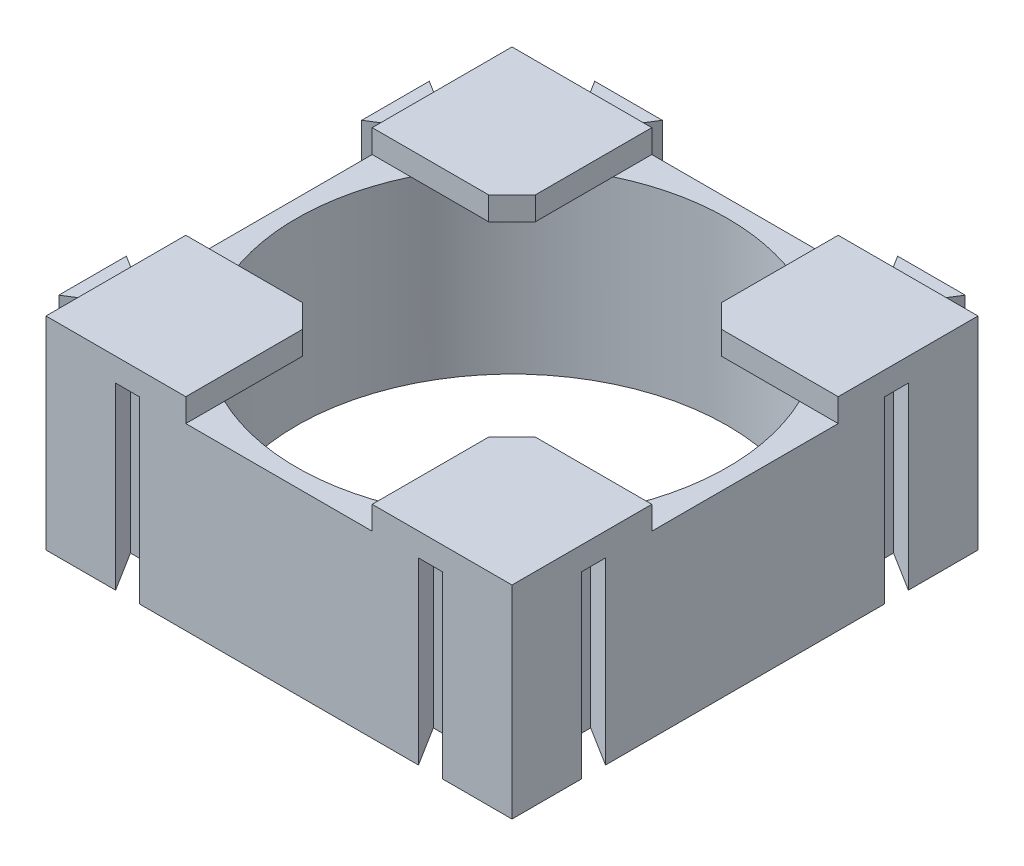
SolidWorks part; units mm, degrees
ref_plane "Alzado" through (0, 0, 0) normal (0, 0, 1) x (1, 0, 0)
ref_plane "Planta" through (0, 0, 0) normal (0, 1, 0) x (1, 0, 0)
ref_plane "Vista lateral" through (0, 0, 0) normal (1, 0, 0) x (0, 0, -1)
ref_plane "Plano1" through (0, 7.7, 0) normal (0, 1, 0) x (1, 0, 0)
sketch "Croquis1" plane through (0, 7.7, 0) normal (0, 1, 0) x (1, 0, 0)
  line L0 (5.9873, -10) -> (4.925, -8.3)
  line L1 (4.925, -8.3) -> (8.075, -8.3)
  line L2 (8.075, -8.3) -> (7.0127, -10)
  line L3 (7.0127, -10) -> (10, -10)
  line L4 (10, -10) -> (10, -7.0127)
  line L5 (10, -7.0127) -> (8.3, -8.075)
  line L6 (8.3, -8.075) -> (8.3, -4.925)
  line L7 (8.3, -4.925) -> (10, -5.9873)
  line L8 (10, -5.9873) -> (10, 5.9873)
  line L9 (10, 5.9873) -> (8.3, 4.925)
  line L10 (8.3, 4.925) -> (8.3, 8.075)
  line L11 (8.3, 8.075) -> (10, 7.0127)
  line L12 (10, 7.0127) -> (10, 10)
  line L13 (10, 10) -> (7.0127, 10)
  line L14 (7.0127, 10) -> (7.95, 11.5)
  line L15 (7.95, 11.5) -> (5.05, 11.5)
  line L16 (5.05, 11.5) -> (5.9873, 10)
  line L17 (5.9873, 10) -> (-5.9873, 10)
  line L18 (-5.9873, 10) -> (-5.05, 11.5)
  line L19 (-5.05, 11.5) -> (-7.95, 11.5)
  line L20 (-7.95, 11.5) -> (-7.0127, 10)
  line L21 (-7.0127, 10) -> (-10, 10)
  line L22 (-10, 10) -> (-10, 7.0127)
  line L23 (-10, 7.0127) -> (-11.5, 7.95)
  line L24 (-11.5, 7.95) -> (-11.5, 5.05)
  line L25 (-11.5, 5.05) -> (-10, 5.9873)
  line L26 (-10, 5.9873) -> (-10, -5.9873)
  line L27 (-10, -5.9873) -> (-11.5, -5.05)
  line L28 (-11.5, -5.05) -> (-11.5, -7.95)
  line L29 (-11.5, -7.95) -> (-10, -7.0127)
  line L30 (-10, -7.0127) -> (-10, -10)
  line L31 (-10, -10) -> (-7.0127, -10)
  line L32 (-7.0127, -10) -> (-8.075, -8.3)
  line L33 (-8.075, -8.3) -> (-4.925, -8.3)
  line L34 (-4.925, -8.3) -> (-5.9873, -10)
  line L35 (-5.9873, -10) -> (5.9873, -10)
extrude "Saliente-Extruir1" add sketch "Croquis1" against normal blind 7.7
sketch "Croquis2" plane through (0, 7.7, 0) normal (0, 1, 0) x (-1, 0, 0)
  line L0 (-10, -4) -> (-4, -4)
  line L1 (-4, -4) -> (-4, -10)
  line L2 (-4, -10) -> (-10, -10)
  line L3 (-10, -10) -> (-10, -4)
extrude "Saliente-Extruir2" add sketch "Croquis2" along normal blind 1
sketch "Croquis3" plane through (0, 7.7, 0) normal (0, 1, 0) x (-1, 0, 0)
  line L0 (-4, 10) -> (-4, 4)
  line L1 (-4, 4) -> (-10, 4)
  line L2 (-10, 4) -> (-10, 10)
  line L3 (-10, 10) -> (-4, 10)
extrude "Saliente-Extruir3" add sketch "Croquis3" along normal blind 1
sketch "Croquis4" plane through (0, 7.7, 0) normal (0, 1, 0) x (-1, 0, 0)
  line L0 (4, 10) -> (10, 10)
  line L1 (10, 10) -> (10, 4)
  line L2 (10, 4) -> (4, 4)
  line L3 (4, 4) -> (4, 10)
extrude "Saliente-Extruir4" add sketch "Croquis4" along normal blind 1
sketch "Croquis5" plane through (0, 7.7, 0) normal (0, 1, 0) x (-1, 0, 0)
  line L0 (4, -10) -> (4, -4)
  line L1 (4, -4) -> (10, -4)
  line L2 (10, -4) -> (10, -10)
  line L3 (10, -10) -> (4, -10)
extrude "Saliente-Extruir5" add sketch "Croquis5" along normal blind 1
hole_wizard "Diámetro de taladro Ø18.5 (18.5)1" positions "Croquis7" profile "Croquis6" hole size "Ø18.5" standard "Ansi Metric"
sketch "Croquis7" plane through (0, 0, 0) normal (0, -1, 0) x (-1, 0, 0)
  point P0 (0, 0)
sketch "Croquis6" plane through (0, 0, 0) normal (1, 0, 0) x (0, 0, -1)
  line L0 (0, 0) -> (0, 7.7)
  line L1 (0, 7.7) -> (9.25, 7.7)
  line L2 (9.25, 7.7) -> (9.25, 0)
  line L5 (9.25, 0) -> (0, 0)
  line L10 (0, 7.7) -> (-9.25, 7.7) construction
  line L11 (0, -6.35) -> (0, 107.95) construction
  dimension "Diámetro de taladro" = 18.5
  dimension "Profundidad de taladro" = 7.7
  dimension "Ángulo de perforador" = 180
chamfer "Chaflán1" distance 1 angle 45 4 edges at (-4, 8.2, -4) (-4, 8.2, 4) (4, 8.2, -4) (4, 8.2, 4)
